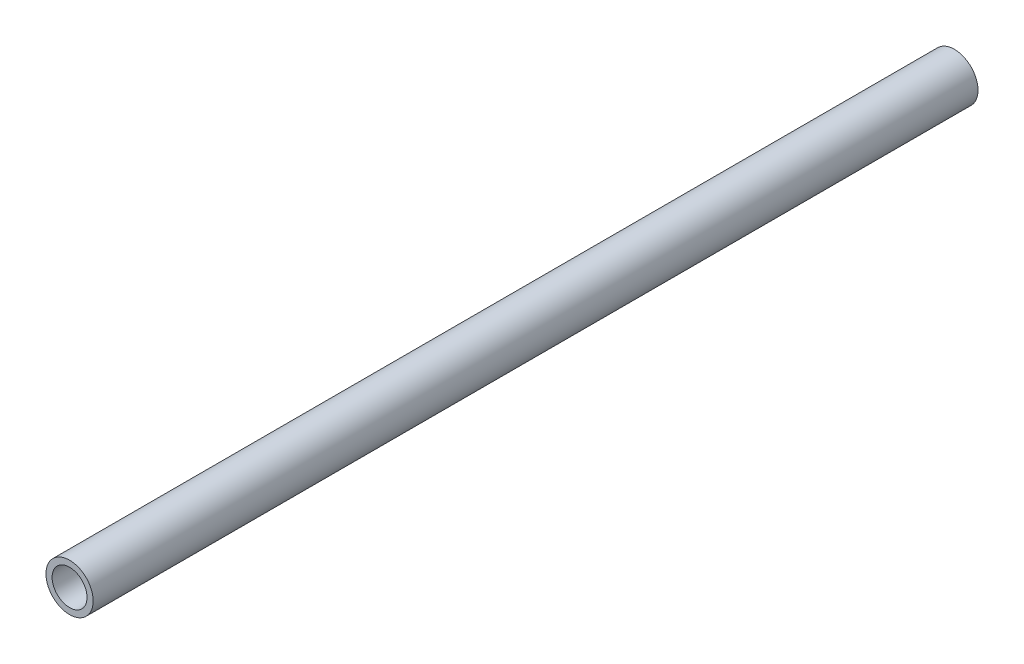
SolidWorks part; units mm, degrees
ref_plane "Front Plane" through (0, 0, 0) normal (0, 0, 1) x (1, 0, 0)
ref_plane "Top Plane" through (0, 0, 0) normal (0, 1, 0) x (1, 0, 0)
ref_plane "Right Plane" through (0, 0, 0) normal (1, 0, 0) x (0, 0, -1)
sketch "Sketch1" plane through (0, 0, 0) normal (0, 0, 1) x (1, 0, 0)
  circle A0 centre (0, 0) radius 10.668
  dimension "Pipe OD" = 21.336
extrude "Extrude-Thin1" add sketch "Sketch1" along normal mid plane 400 thin thin type one direction reverse wall 2.7686
